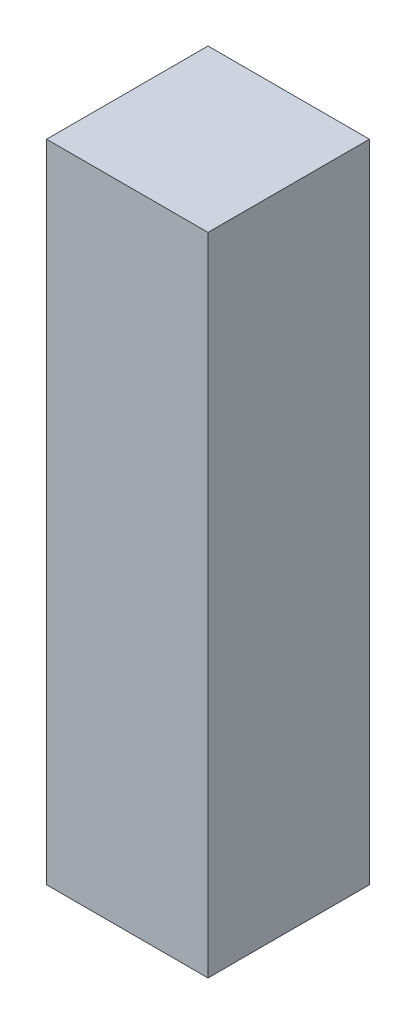
SolidWorks part; units mm, degrees
material "1023 Carbon Steel Sheet (SS)"
ref_plane "Front Plane" through (0, 0, 0) normal (0, 0, 1) x (1, 0, 0)
ref_plane "Top Plane" through (0, 0, 0) normal (0, 1, 0) x (1, 0, 0)
ref_plane "Right Plane" through (0, 0, 0) normal (1, 0, 0) x (0, 0, -1)
sketch "Sketch1" plane through (0, 0, 0) normal (0, 1, 0) x (1, 0, 0)
  line L1 (-1.5875, -1.5875) -> (1.5875, -1.5875)
  line L2 (-1.5875, -1.5875) -> (-1.5875, 1.5875)
  line L3 (-1.5875, 1.5875) -> (1.5875, 1.5875)
  line L4 (1.5875, -1.5875) -> (1.5875, 1.5875)
  line L5 (-1.5875, -1.5875) -> (1.5875, 1.5875) construction
  line L6 (-1.5875, 1.5875) -> (1.5875, -1.5875) construction
  point P0 (0, 0)
  dimension "D1" = 3.175
extrude "Boss-Extrude1" add sketch "Sketch1" along normal blind 12.7
